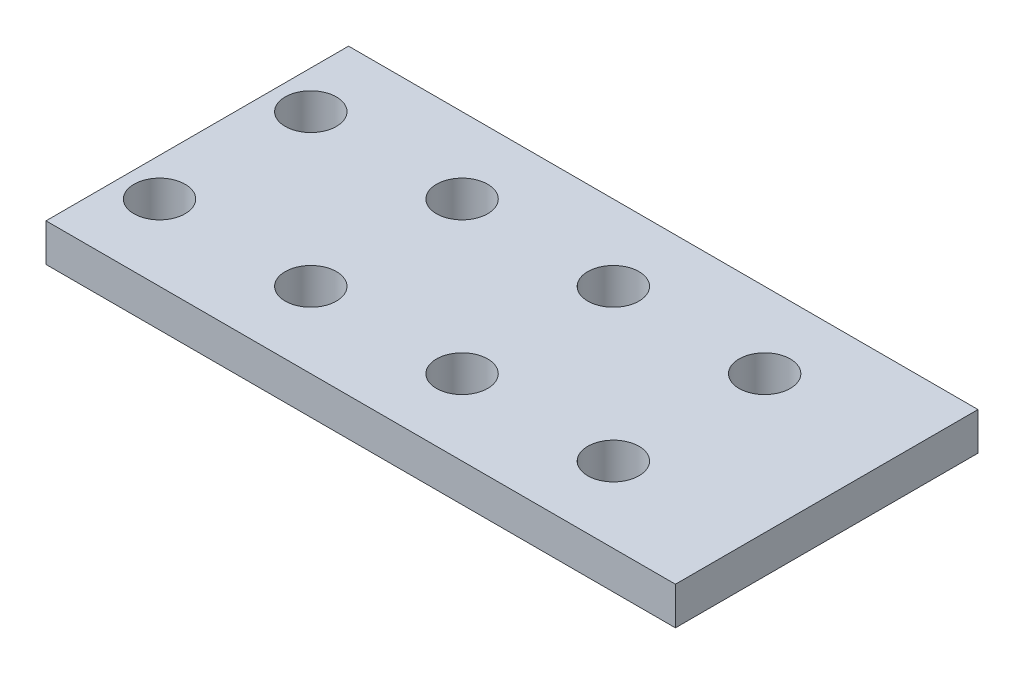
SolidWorks part; units mm, degrees
other "DetailItem1"
other "DetailItem2"
other "DetailItem3"
material "AISI 316 Stainless Steel Sheet (SS)"
ref_plane "Front Plane" through (0, 0, 0) normal (0, 0, 1) x (1, 0, 0)
ref_plane "Top Plane" through (0, 0, 0) normal (0, 1, 0) x (1, 0, 0)
ref_plane "Right Plane" through (0, 0, 0) normal (1, 0, 0) x (0, 0, -1)
ref_plane "40K Bottom Cold head Location" through (0, 87.18, 0) normal (0, 1, 0) x (1, 0, 0)
ref_plane "Top_Connection_Plane" through (34.5, 0, 0) normal (1, 0, 0) x (0, 0, -1)
ref_plane "Bottom_Connection_Plane" through (80.58, 0, 0) normal (1, 0, 0) x (0, 0, -1)
sketch "Sketch1" plane through (0, 0, 0) normal (0, 1, 0) x (1, 0, 0)
  line L0 (72.84, 17.5) -> (72.84, -17.5)
  line L5 (20, 12.7) -> (75, 12.7)
  line L6 (20, 12.7) -> (20, -12.7)
  line L7 (20, -12.7) -> (75, -12.7)
  line L8 (75, 12.7) -> (75, -12.7)
  line L9 (72.84, 17.5) -> (75, 17.5)
  line L10 (75, 17.5) -> (75, 12.7)
  line L11 (72.84, -17.5) -> (75, -17.5)
  line L12 (75, -17.5) -> (75, -12.7)
  circle A0 centre (23.18, 6.35) radius 2.15
  circle A1 centre (35.88, 6.35) radius 2.15
  circle A2 centre (48.58, 6.35) radius 2.15
  circle A3 centre (35.88, -6.35) radius 2.15
  circle A4 centre (48.58, -6.35) radius 2.15
  circle A5 centre (23.18, -6.35) radius 2.15
  circle A6 centre (61.28, 6.35) radius 2.15
  circle A7 centre (61.28, -6.35) radius 2.15
  point P11 (72.84, 0)
  point P12 (75, 0)
  dimension "D5" = 4.3
  dimension "55" = 55
  dimension "D2" = 25.4
  dimension "D3" = 6.35
  dimension "D4" = 3.18
  dimension "D6" = 12.7
  dimension "D7" = 12.7
  dimension "D10" = 20
  dimension "D11" = 12.7
  dimension "D12" = 35
  dimension "D13" = 2.16
  dimension "D14" = 12.7
  dimension "D8" = 3
  dimension "D9" = 2
extrude "Boss-Extrude2" add sketch "Sketch1" along normal blind 3.175 separate body contours L6 L7 L0 L5 A5 A4 A3 A2 A1 A0
sketch "Sketch2" plane through (0, 87.18, 0) normal (0, 1, 0) x (1, 0, 0)
  line L0 (0, 26) -> (0, -26) construction
  line L1 (0, 0) -> (12.8199, 30.95) construction
  line L2 (0.25, 38.4992) -> (0.25, 26.2488)
  line L3 (0.25, -38.4992) -> (0.25, -26.2488)
  line L4 (-12.8199, 30.95) -> (0, 0) construction
  line L5 (-0.25, 38.4992) -> (-0.25, 26.2488)
  line L6 (-28.5, 43.4992) -> (28.5, 43.4992)
  line L7 (-38.5, 33.4992) -> (-38.5, -33.4992)
  line L8 (-28.5, -43.4992) -> (28.5, -43.4992)
  line L9 (38.5, 33.4992) -> (38.5, -33.4992)
  line L10 (-0.25, -26.2488) -> (-0.25, -38.4992)
  line L11 (22.0842, 33.4992) -> (25.2921, 27.9429) construction
  line L12 (25.2921, 27.9429) -> (31.7079, 27.9429) construction
  line L13 (31.7079, 27.9429) -> (34.9158, 33.4992) construction
  line L14 (34.9158, 33.4992) -> (31.7079, 39.0554) construction
  line L15 (31.7079, 39.0554) -> (25.2921, 39.0554) construction
  line L16 (25.2921, 39.0554) -> (22.0842, 33.4992) construction
  line L17 (25.2921, 39.0554) -> (31.7079, 27.9429) construction
  line L18 (0.25, 38.4992) -> (0.25, 43.4992)
  line L19 (-0.25, 38.4992) -> (-0.25, 43.4992)
  line L20 (0.25, -38.4992) -> (0.25, -43.4992)
  line L21 (-0.25, -38.4992) -> (-0.25, -43.4992)
  circle A0 centre (0, 0) radius 26
  circle A1 centre (12.8199, 30.95) radius 2.25
  circle A2 centre (30.95, 12.8199) radius 2.25
  circle A3 centre (30.95, -12.8199) radius 2.25
  circle A4 centre (12.8199, -30.95) radius 2.25
  circle A5 centre (-12.8199, -30.95) radius 2.25
  circle A6 centre (-30.95, -12.8199) radius 2.25
  circle A7 centre (-30.95, 12.8199) radius 2.25
  circle A8 centre (-12.8199, 30.95) radius 2.25
  circle A9 centre (0, 0) radius 38.5
  circle A10 centre (0, 0) radius 26.25
  circle A11 centre (-12.8199, -30.95) radius 2.25
  circle A12 centre (-30.95, -12.8199) radius 2.25
  circle A13 centre (-30.95, 12.8199) radius 2.25
  circle A14 centre (-12.8199, 30.95) radius 2.25
  circle A15 centre (-28.5, 33.4992) radius 3.2639
  circle A16 centre (28.5, 33.4992) radius 3.2639
  circle A17 centre (-28.5, -33.4992) radius 3.2639
  circle A18 centre (28.5, -33.4992) radius 3.2639
  circle A19 centre (28.5, 33.4992) radius 4.7625 construction
  circle A20 centre (28.5, 33.4992) radius 2.3269 construction
  arc A21 (-38.5, -33.4992) -> (-28.5, -43.4992) centre (-28.5, -33.4992) ccw
  arc A22 (28.5, -43.4992) -> (38.5, -33.4992) centre (28.5, -33.4992) ccw
  arc A23 (-28.5, 43.4992) -> (-38.5, 33.4992) centre (-28.5, 33.4992) ccw
  arc A24 (28.5, 43.4992) -> (38.5, 33.4992) centre (28.5, 33.4992) cw
  point P25 (0, 0)
  dimension "D1" = 52
  dimension "D3" = 4.5
  dimension "D8" = 77
  dimension "D9" = 52.5
  dimension "D13" = 6.5278
  dimension "D20" = 9.525
  dimension "D24" = 10
  dimension "D2" = 33.5
  dimension "D4" = 22.5
  dimension "D6" = 33.5
  dimension "D7" = 33.5
  dimension "D10" = 0.25
  dimension "D11" = 5
  dimension "D12" = 5
  dimension "D14" = 10
  dimension "D15" = 10
  dimension "D16" = 10
  dimension "D17" = 10
  dimension "D18" = 5
  dimension "D19" = 0.25
  dimension "D21" = 11.1125
  dimension "D22" = 11.1125
  dimension "D23" = 11.1125
  dimension "D5" = 8
equation "\"D7@Sketch2\"=\"D2@Sketch2\""
equation "\"D6@Sketch2\"=\"D2@Sketch2\""
equation "\"Distance_From_Cold_Center\"=20"
equation "\"D10@Sketch1\"=\"Distance_From_Cold_Center\""
equation "\"D11@Sketch1\"=\"D2@Sketch1\"/2"
equation "\"Inside_Cold_Rod_Dia\"=52"
equation "\"D1@Sketch2\"=\"Inside_Cold_Rod_Dia\""
equation "\"40K_Cold_Head_Dia\"=77"
equation "\"D8@Sketch2\"=\"40K_Cold_Head_Dia\""
equation "\"D14@Sketch1\"=\"D6@Sketch1\""
equation "\"D15@Sketch2\"=\"D14@Sketch2\""
equation "\"D16@Sketch2\"=\"D15@Sketch2\""
equation "\"D17@Sketch2\"=\"D16@Sketch2\""
equation "\"D12@Sketch2\"=\"D11@Sketch2\""
equation "\"D19@Sketch2\"=\"D10@Sketch2\""
equation "\"D22@Sketch2\"=\"D21@Sketch2\""
equation "\"D23@Sketch2\"=\"D22@Sketch2\""
